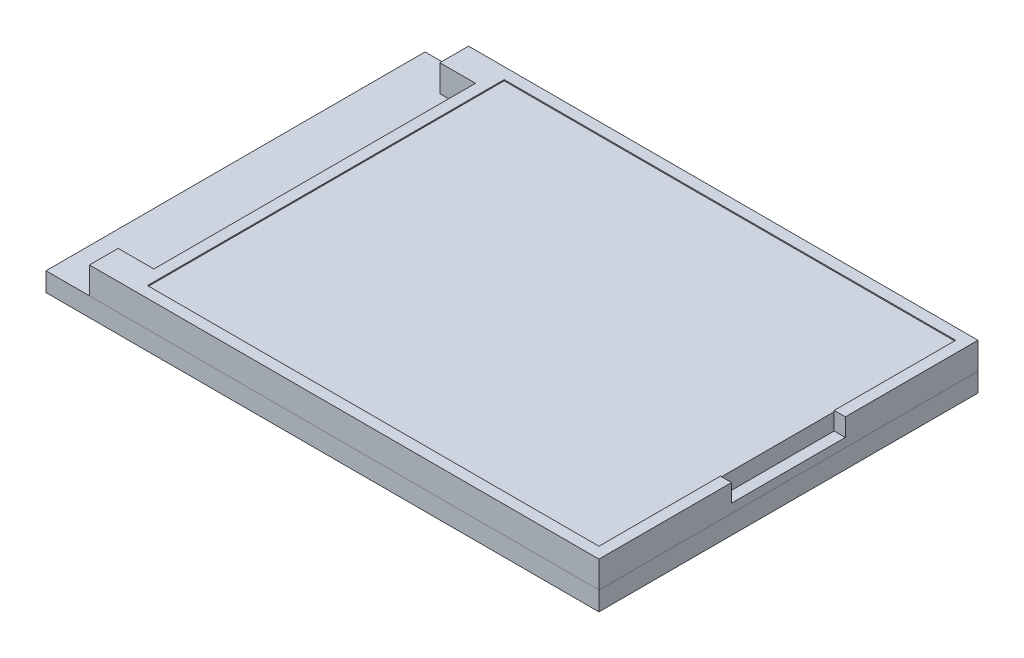
SolidWorks part; units mm, degrees
ref_plane "Front Plane" through (0, 0, 0) normal (0, 0, 1) x (1, 0, 0)
ref_plane "Top Plane" through (0, 0, 0) normal (0, 1, 0) x (1, 0, 0)
ref_plane "Right Plane" through (0, 0, 0) normal (1, 0, 0) x (0, 0, -1)
sketch "Sketch1" plane through (0, 0, 0) normal (0, 1, 0) x (1, 0, 0)
  line L1 (-24.8, 17) -> (24.8, 17)
  line L2 (-24.8, 17) -> (-24.8, -17)
  line L3 (-24.8, -17) -> (24.8, -17)
  line L4 (24.8, 17) -> (24.8, -17)
  line L5 (-24.8, 17) -> (24.8, -17) construction
  line L6 (-24.8, -17) -> (24.8, 17) construction
  point P0 (0, 0)
  dimension "D1" = 34
  dimension "D2" = 49.6
extrude "Boss-Extrude1" add sketch "Sketch1" along normal blind 1.7
sketch "Sketch3" plane through (0, 1.7, 0) normal (0, 1, 0) x (1, 0, 0)
  line L0 (-24.8, -17) -> (24.8, -17) construction
  line L1 (24.8, 17) -> (-20.9, 17)
  line L2 (24.8, 17) -> (24.8, -17)
  line L3 (24.8, -17) -> (-20.9, -17)
  line L4 (-20.9, 17) -> (-20.9, -17)
  line L5 (-24.8, 0) -> (24.8, 0) construction
  line L6 (-24.8, 17) -> (-24.8, -17) construction
  line L7 (-17.7, 0) -> (-20.9, 0) construction
  line L8 (-20.9, 14.425) -> (-17.7, 14.425)
  line L9 (-20.9, 14.425) -> (-20.9, -14.425)
  line L10 (-20.9, -14.425) -> (-17.7, -14.425)
  line L11 (-17.7, 14.425) -> (-17.7, -14.425)
  line M1 (24.8, -17) -> (24.8, 17)
  line M2 (24.8, 17) -> (-24.8, 17)
  line M4 (-24.8, -17) -> (24.8, -17)
  dimension "D1" = 45.7
  dimension "D2" = 28.85
  dimension "D3" = 3.2
extrude "Boss-Extrude2" add sketch "Sketch3" along normal blind 2.4 separate body contours L8 L11 L10 L4 M4 M1 M2
sketch "Sketch4" plane through (0, 4.1, 0) normal (0, 1, 0) x (1, 0, 0)
  line L0 (-24.8, 0) -> (24.8, 0) construction
  line L1 (-24.8, 17) -> (-24.8, -17) construction
  line L2 (24.8, -17) -> (24.8, 17) construction
  line L3 (-16.7, 0) -> (23.8, 0) construction
  line L4 (-16.7, 16) -> (23.8, 16)
  line L5 (-16.7, 16) -> (-16.7, -16)
  line L6 (-16.7, -16) -> (23.8, -16)
  line L7 (23.8, 16) -> (23.8, -16)
  line L8 (24.8, 17) -> (-20.9, 17) construction
  line L9 (-17.7, 14.425) -> (-17.7, -14.425) construction
  dimension "D1" = 1
  dimension "D2" = 1
  dimension "D3" = 1
extrude "Cut-Extrude1" cut sketch "Sketch4" against normal blind 0.1
sketch "Sketch5" plane through (0, 4.1, 0) normal (0, 1, 0) x (1, 0, 0)
  line L0 (24.8, 0) -> (-24.8, 0) construction
  line L1 (24.8, -17) -> (24.8, 17) construction
  line L2 (-24.8, 17) -> (-24.8, -17) construction
  line L3 (23.8, -16) -> (23.8, 16) construction
  line L4 (24.8, 5.1) -> (23.8, 5.1)
  line L5 (24.8, 5.1) -> (24.8, -5.1)
  line L6 (24.8, -5.1) -> (23.8, -5.1)
  line L7 (23.8, 5.1) -> (23.8, -5.1)
  line L8 (24.8, 0) -> (23.8, 0) construction
  dimension "D1" = 10.2
extrude "Cut-Extrude2" cut sketch "Sketch5" against normal blind 1.6
